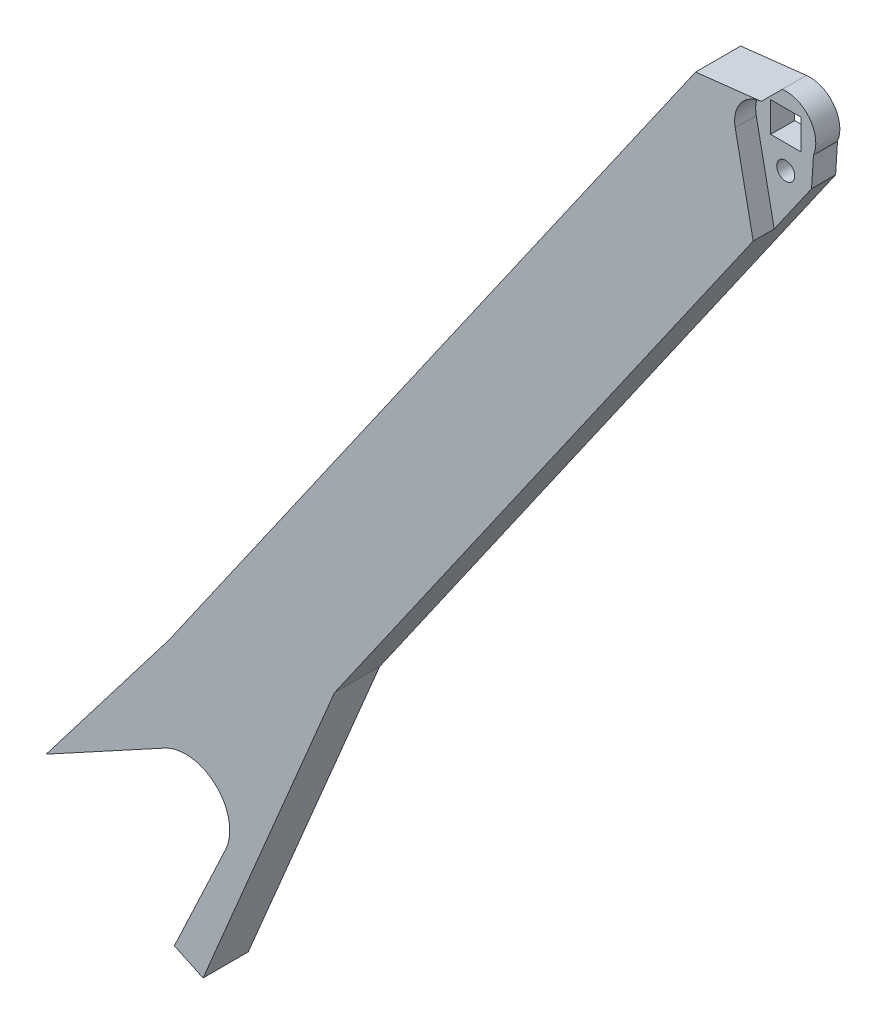
SolidWorks part; units mm, degrees
ref_plane "Front Plane" through (0, 0, 0) normal (0, 0, 1) x (1, 0, 0)
ref_plane "Top Plane" through (0, 0, 0) normal (0, 1, 0) x (1, 0, 0)
ref_plane "Right Plane" through (0, 0, 0) normal (1, 0, 0) x (0, 0, -1)
sketch "Sketch1" plane through (0, 0, 0) normal (0, 0, 1) x (1, 0, 0)
  line L7 (37.8872, 1.4702) -> (27.0719, -21.5122)
  line L8 (0, 0) -> (25.0037, 13.617)
  line L13 (60.9078, 41.7225) -> (33.1383, -24.367)
  line L14 (33.1383, -24.367) -> (27.0719, -21.5122)
  line L15 (42.9892, -0.9225) -> (60.9078, 41.7225) construction
  line L17 (0, 0) -> (-15.5771, 0) construction
  line L29 (151.0381, 194.9153) -> (137.1564, 193.3472)
  line L31 (157.605, 186.1456) -> (157.205, 179.8082)
  line L32 (157.205, 179.8082) -> (60.9078, 41.7225)
  line L34 (0, 0) -> (25.8991, 33.8095)
  line L35 (25.8991, 33.8095) -> (137.1564, 193.3472)
  arc A1 (37.8872, 1.4702) -> (25.0037, 13.617) centre (29.4588, 5.4365) ccw
  arc A4 (157.605, 186.1456) -> (151.0381, 194.9153) centre (151.7508, 188.6054) ccw
  arc A5 (157.605, 186.1456) -> (151.0381, 194.9153) centre (151.7508, 188.6054) ccw construction
  dimension "D1" = 208.573
  dimension "D2" = 9.315
  dimension "D3" = 25.4
  dimension "D4" = 5.4365
  dimension "D5" = 33.655
extrude "Boss-Extrude1" add sketch "Sketch1" along normal blind 9.525
sketch "Sketch2" plane through (0, 0, 9.525) normal (0, 0, 1) x (1, 0, 0)
  line L0 (149.3208, 168.5027) -> (145.5258, 187.3521) construction
  line L1 (157.205, 179.8082) -> (149.3208, 168.5027) construction
  line L2 (157.605, 186.1456) -> (157.205, 179.8082) construction
  line L3 (149.3208, 168.5027) -> (145.5258, 187.3521)
  line L4 (157.205, 179.8082) -> (149.3208, 168.5027)
  line L5 (157.605, 186.1456) -> (157.205, 179.8082)
  arc A0 (157.605, 186.1456) -> (151.0381, 194.9153) centre (151.7508, 188.6054) ccw construction
  arc A1 (151.0381, 194.9153) -> (145.5258, 187.3521) centre (151.7508, 188.6054) ccw construction
  arc A2 (157.605, 186.1456) -> (151.0381, 194.9153) centre (151.7508, 188.6054) ccw
  arc A3 (151.0381, 194.9153) -> (145.5258, 187.3521) centre (151.7508, 188.6054) ccw
extrude "Cut-Extrude1" cut sketch "Sketch2" against normal blind 4.445
sketch "Sketch3" plane through (0, 0, 5.08) normal (0, 0, 1) x (1, 0, 0)
  line L0 (154.9258, 185.4304) -> (148.5758, 185.4304) construction
  line L1 (154.9258, 191.7804) -> (154.9258, 185.4304) construction
  line L2 (148.5758, 191.7804) -> (154.9258, 191.7804) construction
  line L3 (148.5758, 185.4304) -> (148.5758, 191.7804) construction
  line L4 (154.9258, 185.4304) -> (148.5758, 185.4304)
  line L5 (154.9258, 191.7804) -> (154.9258, 185.4304)
  line L6 (148.5758, 191.7804) -> (154.9258, 191.7804)
  line L7 (148.5758, 185.4304) -> (148.5758, 191.7804)
  circle A0 centre (151.7508, 180.3504) radius 1.905 construction
  circle A1 centre (151.7508, 180.3504) radius 1.905
extrude "Cut-Extrude2" cut sketch "Sketch3" against normal through all
